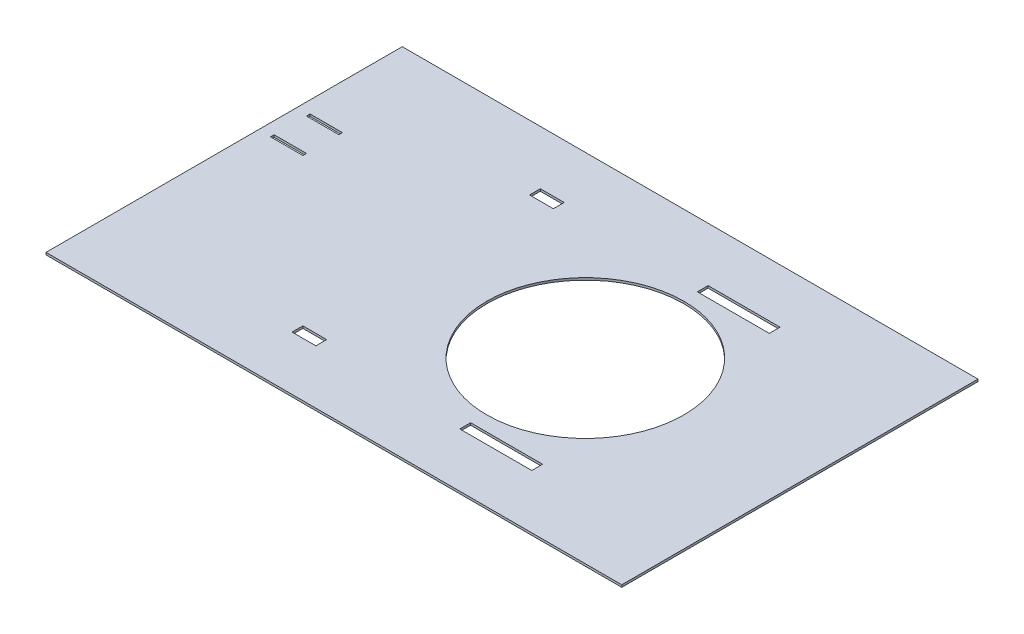
SolidWorks part; units mm, degrees
ref_plane "Front Plane" through (0, 0, 0) normal (0, 0, 1) x (1, 0, 0)
ref_plane "Top Plane" through (0, 0, 0) normal (0, 1, 0) x (1, 0, 0)
ref_plane "Right Plane" through (0, 0, 0) normal (1, 0, 0) x (0, 0, -1)
sketch "Sketch1" plane through (0, 0, 0) normal (0, 1, 0) x (1, 0, 0)
  line L0 (96.8014, -152.4554) -> (96.8014, -166.9771)
  line L1 (96.8014, -166.9771) -> (193.6028, -166.9771)
  line L2 (193.6028, -166.9771) -> (193.6028, -152.4554)
  line L3 (193.6028, -152.4554) -> (96.8014, -152.4554)
  line L4 (-128.8477, 166.9804) -> (-128.8477, 152.4587)
  line L5 (-128.8477, 152.4587) -> (-96.8046, 152.4587)
  line L6 (-96.8046, 152.4587) -> (-96.8046, 166.9804)
  line L7 (-96.8046, 166.9804) -> (-128.8477, 166.9804)
  line L8 (-128.8477, -152.4554) -> (-128.8477, -166.9771)
  line L9 (-128.8477, -166.9771) -> (-96.8046, -166.9771)
  line L10 (-96.8046, -166.9771) -> (-96.8046, -152.4554)
  line L11 (-96.8046, -152.4554) -> (-128.8477, -152.4554)
  line L12 (-370.8461, 99.2292) -> (-370.8461, 94.3886)
  line L13 (-370.8461, 94.3886) -> (-327.281, 94.3886)
  line L14 (-327.281, 94.3886) -> (-327.281, 99.2292)
  line L15 (-327.281, 99.2292) -> (-370.8461, 99.2292)
  line L16 (-370.8461, 50.8235) -> (-370.8461, 45.9796)
  line L17 (-370.8461, 45.9796) -> (-327.281, 45.9796)
  line L18 (-327.281, 45.9796) -> (-327.281, 50.8235)
  line L19 (-327.281, 50.8235) -> (-370.8461, 50.8235)
  line L20 (193.5961, 152.4587) -> (193.5961, 166.9804)
  line L21 (193.5961, 166.9804) -> (96.7964, 166.9804)
  line L22 (96.7964, 166.9804) -> (96.7964, 152.4587)
  line L23 (96.7964, 152.4587) -> (193.5961, 152.4587)
  line L24 (387.2038, -239.5806) -> (387.2038, 239.5806)
  line L25 (-387.2037, -239.5806) -> (387.2038, -239.5806)
  line L26 (-387.2037, 239.5806) -> (-387.2037, -239.5806)
  line L27 (387.2038, 239.5806) -> (-387.2037, 239.5806)
  line L28 (231.1406, 0.0035) -> (231.1406, 0.0042)
  spline S0 degree 3 poles (231.1406, 0.0042) (231.1406, 73.1819) (171.8185, 132.5041) (98.6408, 132.5042) knots 0 0 0 0 0.2 0.2 0.2 0.2
  spline S1 degree 3 poles (98.6408, 132.5042) (25.4631, 132.5043) (-33.8593, 73.1822) (-33.8594, 0.0045) knots 0.2 0.2 0.2 0.2 0.4 0.4 0.4 0.4
  spline S2 degree 3 poles (-33.8594, 0.0045) (-33.8597, -73.1731) (25.4623, -132.4955) (98.6401, -132.4958) knots 0.4 0.4 0.4 0.4 0.6 0.6 0.6 0.6
  spline S3 degree 3 poles (98.6401, -132.4958) (171.8177, -132.4961) (231.1402, -73.1742) (231.1406, 0.0035) knots 0.6 0.6 0.6 0.6 1 1 1 1
extrude "Boss-Extrude1" add sketch "Sketch1" along normal blind 3
